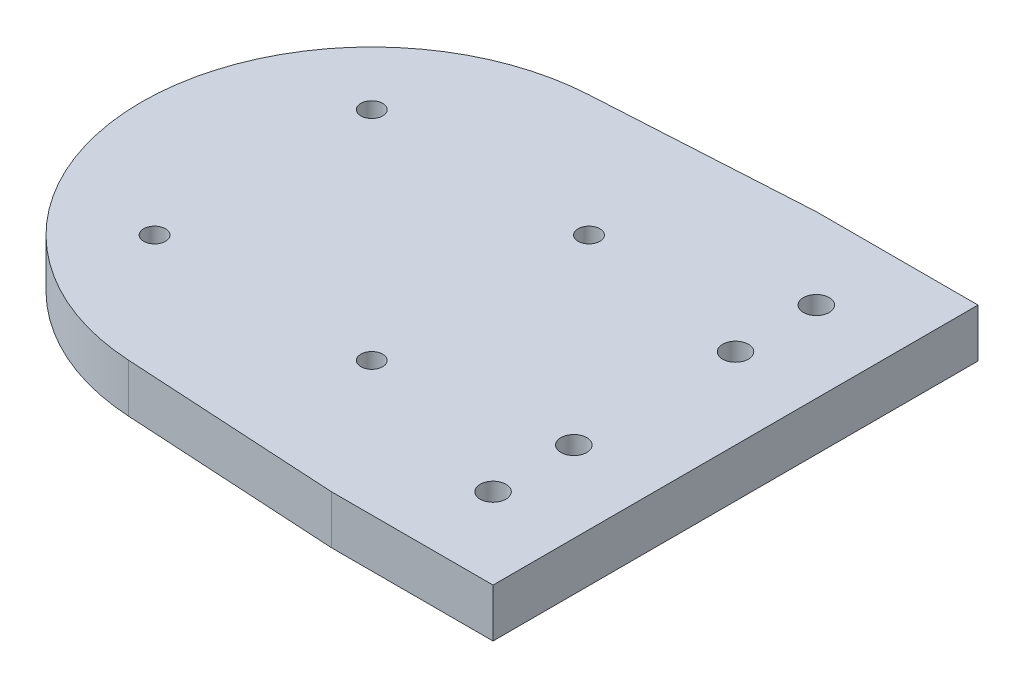
SolidWorks part; units mm, degrees
material "Thornel Mat VMA"
ref_plane "前视基准面" through (0, 0, 0) normal (0, 0, 1) x (1, 0, 0)
ref_plane "上视基准面" through (0, 0, 0) normal (0, 1, 0) x (1, 0, 0)
ref_plane "右视基准面" through (0, 0, 0) normal (1, 0, 0) x (0, 0, -1)
other "Configuration Table"
sketch "草图1" plane through (0, 0, 0) normal (0, 1, 0) x (1, 0, 0)
  line L6 (45, -30) -> (45, 30)
  line L7 (-35.818, 0) -> (83.8138, 0) construction
  line L8 (45, 30) -> (25, 30)
  line L9 (25, 30) -> (-1.6525, 28.4521)
  line L13 (45, -30) -> (25, -30)
  line L14 (25, -30) -> (-1.6525, -28.4521)
  arc A0 (-1.6525, 28.4521) -> (-1.6525, -28.4521) centre (0, 0) ccw
  point P0 (0, 0)
  point P19 (0, 0)
  dimension "D2" = 28.5
  dimension "D1" = 60
  dimension "D3" = 45
  dimension "D4" = 20
extrude "凸台-拉伸1" add sketch "草图1" along normal blind 6
sketch "草图2" plane through (0, 6, 0) normal (0, 1, 0) x (1, 0, 0)
  line L3 (45, -30) -> (45, 30)
  line L4 (45, 30) -> (25, 30)
  line L6 (45, -30) -> (45, 30) construction
  line L11 (25, 30) -> (-1.6525, 28.4521)
  line L13 (-1.6525, -28.4521) -> (25, -30)
  line L15 (25, -30) -> (45, -30)
  circle A0 centre (-13.435, 13.435) radius 1.35
  arc A1 (-1.6525, 28.4521) -> (-1.6525, -28.4521) centre (0, 0) ccw
  arc A2 (-1.6525, 28.4521) -> (-1.6525, -28.4521) centre (0, 0) ccw construction
  circle A3 centre (13.435, 13.435) radius 1.35
  circle A4 centre (13.435, -13.435) radius 1.35
  circle A5 centre (-13.435, -13.435) radius 1.35
  point P16 (0, 0)
  dimension "D3" = 2.7
  dimension "D4" = 19
  dimension "D1" = 0
  dimension "D2" = 4
extrude "切除-拉伸1" cut sketch "草图2" against normal up to surface (6 mm away) up to face at (18.3079, 0, 0)
sketch "草图4" plane through (0, 6, 0) normal (0, 1, 0) x (1, 0, 0)
  line L0 (-33.874, 0) -> (57.1213, 0) construction
  line L5 (45, 30) -> (25, 30)
  line L6 (25, 30) -> (-1.6525, 28.4521)
  line L7 (-1.6525, -28.4521) -> (25, -30)
  line L8 (25, -30) -> (45, -30)
  line L9 (45, -30) -> (45, 30)
  line L10 (45, 30) -> (25, 30) construction
  line L11 (25, 30) -> (-1.6525, 28.4521) construction
  line L12 (-1.6525, -28.4521) -> (25, -30) construction
  line L13 (25, -30) -> (45, -30) construction
  line L14 (45, -30) -> (45, 30) construction
  circle A0 centre (35, 20) radius 1.6
  arc A1 (-1.6525, 28.4521) -> (-1.6525, -28.4521) centre (0, 0) ccw
  arc A2 (-1.6525, 28.4521) -> (-1.6525, -28.4521) centre (0, 0) ccw construction
  circle A3 centre (35, 10) radius 1.6
  circle A4 centre (35, -20) radius 1.6
  circle A5 centre (35, -10) radius 1.6
  dimension "D2" = 3.2
  dimension "D3" = 3.2
  dimension "D4" = 10
  dimension "D5" = 10
  dimension "D6" = 10
  dimension "D1" = 0
extrude "切除-拉伸2" cut sketch "草图4" against normal up to surface (6 mm away) up to face at (-13.435, 0, 14.785)
